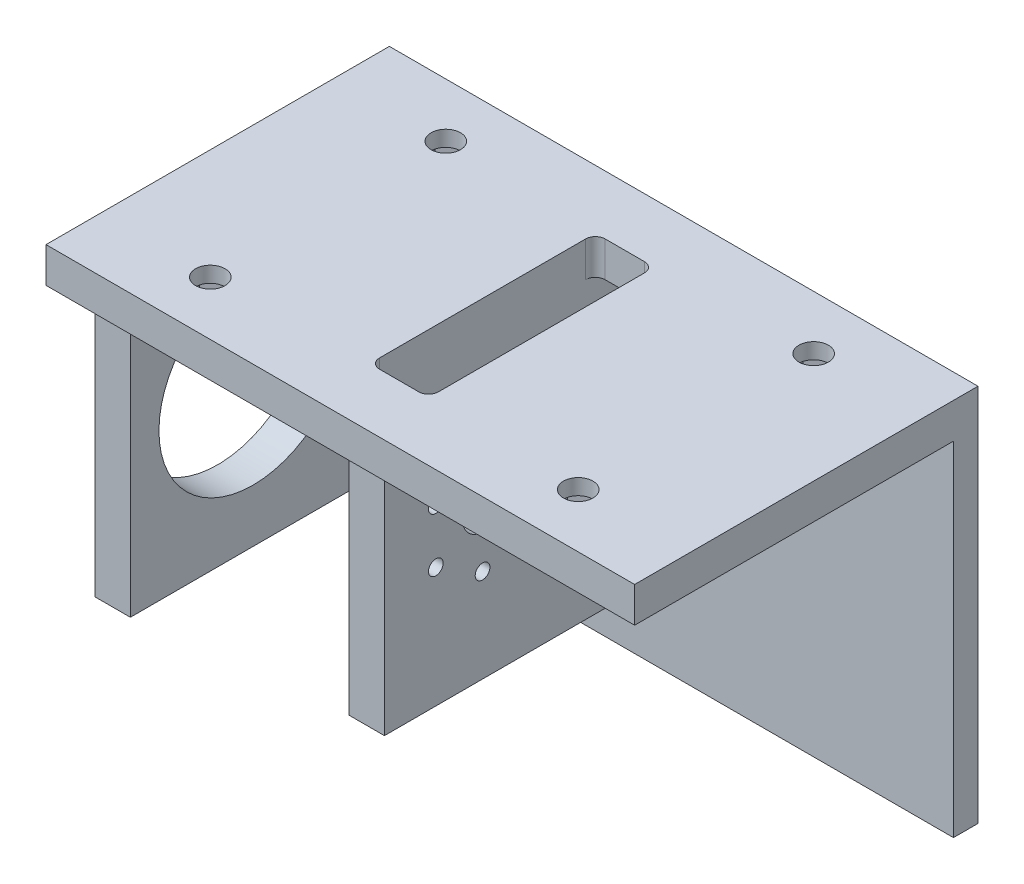
SolidWorks part; units mm, degrees
ref_plane "Front Plane" through (0, 0, 0) normal (0, 0, 1) x (1, 0, 0)
ref_plane "Top Plane" through (0, 0, 0) normal (0, 1, 0) x (1, 0, 0)
ref_plane "Right Plane" through (0, 0, 0) normal (1, 0, 0) x (0, 0, -1)
sketch "Sketch1" plane through (0, 0, 0) normal (0, 1, 0) x (1, 0, 0)
  line L0 (0, 18.2197) -> (0, -18.3609) construction
  line L1 (-19.3496, 0) -> (20.197, 0) construction
  line L2 (-37.5, 0) -> (-37.5, -10) construction
  line L3 (60, 35) -> (-60, 35)
  line L4 (-60, 35) -> (-60, -35)
  line L5 (60, -35) -> (-60, -35)
  line L6 (60, 35) -> (60, -35)
  line L7 (6, 23) -> (-6, 23)
  line L8 (-6, 23) -> (-6, -23)
  line L9 (6, -23) -> (-6, -23)
  line L10 (6, 23) -> (6, -23)
  circle A0 centre (-37.5, 0) radius 10 construction
  circle A6 centre (-37.5, 24) radius 3
  circle A7 centre (-37.5, 24) radius 3.4 construction
  circle A8 centre (-37.5, -24) radius 3
  circle A9 centre (-37.5, -24) radius 3.4 construction
  circle A10 centre (37.5, 24) radius 3
  circle A11 centre (37.5, 24) radius 3.4 construction
  circle A12 centre (37.5, 0) radius 10 construction
  circle A13 centre (37.5, -24) radius 3.4 construction
  circle A14 centre (37.5, -24) radius 3
  point P18 (-60, 0)
  point P20 (0, 35)
  point P21 (0, -35)
  point P33 (-6, 0)
  point P35 (0, -23)
  point P36 (0, 23)
  dimension "D1" = 20
  dimension "D3" = 6.8
  dimension "D4" = 48
  dimension "D5" = 75
  dimension "D2" = 6
  dimension "D6" = 120
  dimension "D7" = 70
  dimension "D8" = 12
  dimension "D9" = 46
extrude "Boss-Extrude1" add sketch "Sketch1" along normal blind 7.2
fillet "Fillet1" radius 2 4 edges at (6, 3.6, 23) (-6, 3.6, 23) (6, 3.6, -23) (-6, 3.6, -23)
sketch "Sketch2" plane through (0, 0, 0) normal (0, -1, 0) x (1, 0, 0)
  line L0 (-60, -35) -> (-60, -30)
  line L1 (-60, -35) -> (-60, 35) construction
  line L2 (-60, -30) -> (60, -30)
  line L3 (60, 35) -> (60, -35) construction
  line L4 (60, -30) -> (60, -35)
  line L5 (60, -35) -> (-60, -35)
  dimension "D1" = 5
extrude "Boss-Extrude2" add sketch "Sketch2" along normal blind 70
sketch "Sketch3" plane through (0, 0, -30) normal (0, 0, 1) x (1, 0, 0)
  line L0 (0, 0) -> (0, -70) construction
  line L1 (60, 0) -> (-60, 0) construction
  line L2 (60, -70) -> (-60, -70) construction
  line L3 (0, -35) -> (-60, -35) construction
  line L4 (-60, -70) -> (-60, 0) construction
  line L5 (0, -35) -> (60, -35) construction
  line L6 (60, -70) -> (60, 0) construction
  line L7 (-9.6, 0) -> (-9.6, -60) construction
  line L8 (30, 0) -> (30, -70) construction
  line L9 (-6, 0) -> (-13.2, 0)
  line L10 (-13.2, 0) -> (-13.2, -60)
  line L11 (-13.2, -60) -> (-6, -60)
  line L12 (-6, 0) -> (-6, -60)
  point P18 (30, -35)
  dimension "D1" = 7.2
  dimension "D2" = 9.6
  dimension "D3" = 60
extrude "Boss-Extrude3" add sketch "Sketch3" along normal blind 50
sketch "Sketch4" plane through (-13.2, 0, 0) normal (-1, 0, 0) x (0, 0, 1)
  line L0 (0, 0) -> (0, -60) construction
  line L1 (20, -60) -> (-30, -60) construction
  line L2 (-30, -30) -> (20, -30) construction
  line L4 (-30, 0) -> (-30, -60) construction
  line L5 (20, 0) -> (20, -60) construction
  circle A0 centre (0, -30) radius 4
  circle A1 centre (0, -30) radius 11 construction
  circle A2 centre (0, -19) radius 1.5
  circle A3 centre (-9.5263, -24.5) radius 1.5
  circle A4 centre (-9.5263, -35.5) radius 1.5
  circle A5 centre (0, -41) radius 1.5
  circle A6 centre (9.5263, -35.5) radius 1.5
  circle A7 centre (9.5263, -24.5) radius 1.5
  point P28 (0, -30)
  dimension "D1" = 8
  dimension "D2" = 22
  dimension "D3" = 3
  dimension "D4" = 6
extrude "Cut-Extrude1" cut sketch "Sketch4" against normal blind 10
sketch "Sketch5" plane through (-13.2, 0, 0) normal (-1, 0, 0) x (0, 0, 1)
  circle A0 centre (0, -30) radius 8.5
  dimension "D1" = 17
extrude "Cut-Extrude2" cut sketch "Sketch5" against normal blind 3
sketch "Sketch6" plane through (0, 0, -30) normal (0, 0, 1) x (1, 0, 0)
  line L1 (-60, 0) -> (-52.8, 0)
  line L2 (-60, 0) -> (-60, -60)
  line L3 (-60, -60) -> (-52.8, -60)
  line L4 (-52.8, 0) -> (-52.8, -60)
  dimension "D1" = 7.2
  dimension "D2" = 60
extrude "Boss-Extrude4" add sketch "Sketch6" along normal blind 55
sketch "Sketch8" plane through (0, 0, 0) normal (0, -1, 0) x (1, 0, 0)
  line L1 (42.7, 27.0022) -> (37.5, 30.0044)
  line L2 (37.5, 30.0044) -> (32.3, 27.0022)
  line L3 (32.3, 27.0022) -> (32.3, 20.9978)
  line L4 (32.3, 20.9978) -> (37.5, 17.9956)
  line L5 (37.5, 17.9956) -> (42.7, 20.9978)
  line L6 (42.7, 20.9978) -> (42.7, 27.0022)
  line L7 (-32.3, 27.0022) -> (-37.5, 30.0044)
  line L8 (-37.5, 30.0044) -> (-42.7, 27.0022)
  line L9 (-42.7, 27.0022) -> (-42.7, 20.9978)
  line L10 (-42.7, 20.9978) -> (-37.5, 17.9956)
  line L11 (-37.5, 17.9956) -> (-32.3, 20.9978)
  line L12 (-32.3, 20.9978) -> (-32.3, 27.0022)
  line L13 (42.7, -20.9978) -> (37.5, -17.9956)
  line L14 (37.5, -17.9956) -> (32.3, -20.9978)
  line L15 (32.3, -20.9978) -> (32.3, -27.0022)
  line L16 (32.3, -27.0022) -> (37.5, -30.0044)
  line L17 (37.5, -30.0044) -> (42.7, -27.0022)
  line L18 (42.7, -27.0022) -> (42.7, -20.9978)
  line L19 (-32.3, -20.9978) -> (-37.5, -17.9956)
  line L20 (-37.5, -17.9956) -> (-42.7, -20.9978)
  line L21 (-42.7, -20.9978) -> (-42.7, -27.0022)
  line L22 (-42.7, -27.0022) -> (-37.5, -30.0044)
  line L23 (-37.5, -30.0044) -> (-32.3, -27.0022)
  line L24 (-32.3, -27.0022) -> (-32.3, -20.9978)
  circle A0 centre (37.5, 24) radius 5.2 construction
  circle A1 centre (-37.5, 24) radius 5.2 construction
  circle A2 centre (37.5, -24) radius 5.2 construction
  circle A3 centre (-37.5, -24) radius 5.2 construction
  dimension "D1" = 10.4
  dimension "D2" = 10.4
  dimension "D3" = 10.4
  dimension "D4" = 10.4
extrude "Cut-Extrude4" cut sketch "Sketch8" against normal blind 4
sketch "Sketch10" plane through (-6, 0, 0) normal (1, 0, 0) x (0, 0, -1)
  circle A0 centre (0, -30) radius 4
  circle A1 centre (0, -30) radius 4 construction
extrude "Cut-Extrude5" cut sketch "Sketch10" against normal blind 60
sketch "Sketch11" plane through (-60, 0, 0) normal (-1, 0, 0) x (0, 0, 1)
  circle A0 centre (0, -30) radius 19.175
  dimension "D1" = 38.35
extrude "Cut-Extrude6" cut sketch "Sketch11" against normal up to surface (7.2 mm away) up to face at (-52.8, -34, 0)
